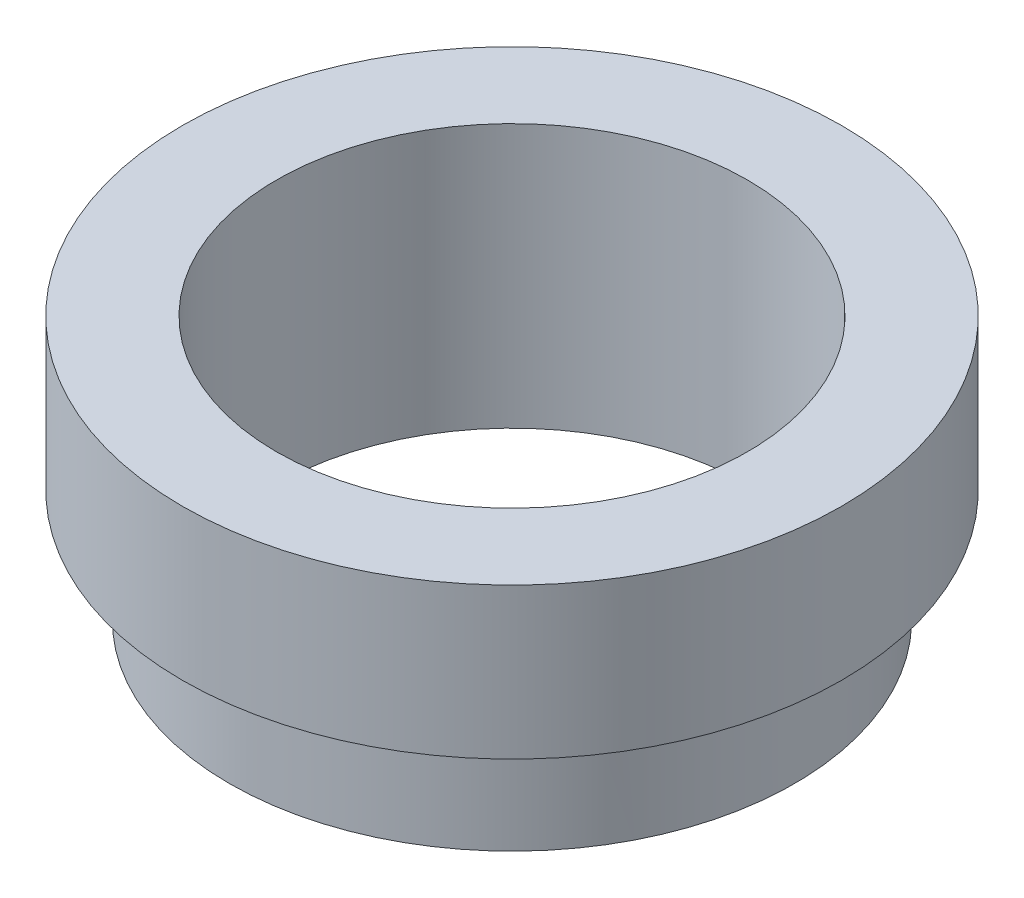
SolidWorks part; units mm, degrees
ref_plane "Front Plane" through (0, 0, 0) normal (0, 0, 1) x (1, 0, 0)
ref_plane "Top Plane" through (0, 0, 0) normal (0, 1, 0) x (1, 0, 0)
ref_plane "Right Plane" through (0, 0, 0) normal (1, 0, 0) x (0, 0, -1)
sketch "Sketch1" plane through (0, 0, 0) normal (0, 1, 0) x (1, 0, 0)
  circle A0 centre (0, 0) radius 12.5
  circle A1 centre (0, 0) radius 17.5
  dimension "D1" = 35
  dimension "D2" = 25
extrude "Boss-Extrude1" add sketch "Sketch1" along normal blind 8
sketch "Sketch2" plane through (0, 0, 0) normal (0, -1, 0) x (1, 0, 0)
  circle A0 centre (0, 0) radius 15
  circle A1 centre (0, 0) radius 12.5
  dimension "D1" = 30
  dimension "D2" = 25
extrude "Boss-Extrude2" add sketch "Sketch2" along normal blind 6
